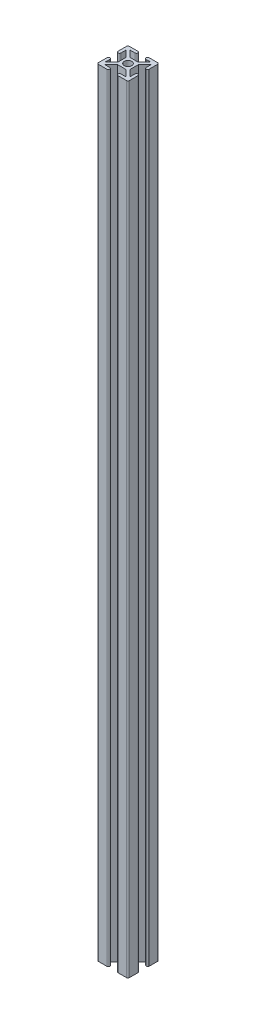
SolidWorks part; units mm, degrees
ref_plane "Alzado" through (0, 0, 0) normal (0, 0, 1) x (1, 0, 0)
ref_plane "Planta" through (0, 0, 0) normal (0, 1, 0) x (1, 0, 0)
ref_plane "Vista lateral" through (0, 0, 0) normal (1, 0, 0) x (0, 0, -1)
sketch "Croquis1" plane through (0, 0, 0) normal (0, 1, 0) x (1, 0, 0)
  line L0 (-15.8949, 10.1863) -> (-15.8949, 11.6113) construction
  line L1 (3.158, -5.9637) -> (7.883, -5.9637)
  line L2 (-17.3199, 19.7613) -> (-17.3199, 11.6113)
  line L3 (-15.8949, 21.1863) -> (-7.7449, 21.1863)
  line L4 (3.1051, 21.1863) -> (11.2551, 21.1863)
  line L5 (-12.417, -5.9637) -> (-7.692, -5.9637)
  line L6 (-8.3199, 10.1863) -> (-8.3199, 2.1863)
  line L7 (-17.267, 0.7613) -> (-17.267, -7.3887)
  line L8 (-15.8684, -8.7872) -> (-7.692, -8.8137)
  line L9 (12.6801, 19.7613) -> (12.6801, 11.715)
  line L10 (-14.4699, 16.3363) -> (-14.4699, 11.6113)
  line L11 (12.6801, 0.865) -> (12.6801, -7.3887)
  line L12 (-6.3199, 19.7613) -> (-7.7449, 19.7613) construction
  line L13 (3.158, -8.8137) -> (11.2551, -8.8137)
  line L14 (-12.4699, 18.3363) -> (-7.7449, 18.3363)
  line L15 (-14.4699, 0.7613) -> (-14.4699, -3.9637)
  line L16 (1.6801, 19.7613) -> (3.1051, 19.7613) construction
  line L17 (3.1051, 18.3363) -> (7.8301, 18.3363)
  line L18 (11.2551, 10.29) -> (11.2551, 11.715) construction
  line L19 (-6.3199, 12.1863) -> (-12.4699, 18.3363)
  line L20 (9.8301, 16.3363) -> (9.8301, 11.715)
  line L21 (11.2551, 2.29) -> (11.2551, 0.865) construction
  line L22 (-8.3199, 10.1863) -> (-14.4699, 16.3363)
  line L23 (9.8301, 0.865) -> (9.8301, -3.9637)
  line L24 (1.733, -7.3887) -> (3.158, -7.3887) construction
  line L25 (-8.3199, 2.1863) -> (-14.4699, -3.9637)
  line L26 (-6.3199, 12.1863) -> (1.6801, 12.1863)
  line L27 (1.6801, 12.1863) -> (7.8301, 18.3363)
  line L28 (-15.8684, 2.1863) -> (-15.8684, 0.7613) construction
  line L29 (-12.417, -5.9637) -> (-6.267, 0.1863)
  line L30 (-6.267, 0.1863) -> (1.733, 0.1863)
  line L31 (1.733, 0.1863) -> (7.883, -5.9637)
  line L32 (-6.267, -7.3887) -> (-7.692, -7.3887) construction
  line L33 (3.6801, 2.1863) -> (9.8301, -3.9637)
  line L34 (3.6801, 10.1863) -> (9.8301, 16.3363)
  line L35 (3.6801, 10.1863) -> (3.6801, 2.1863)
  circle A0 centre (-2.267, 6.1863) radius 3.645
  arc A1 (-17.3199, 11.6113) -> (-14.4699, 11.6113) centre (-15.8949, 11.6113) ccw
  arc A2 (-7.7449, 18.3363) -> (-7.7449, 21.1863) centre (-7.7449, 19.7613) ccw
  arc A3 (3.1051, 21.1863) -> (3.1051, 18.3363) centre (3.1051, 19.7613) ccw
  arc A4 (9.8301, 11.715) -> (12.6801, 11.715) centre (11.2551, 11.715) ccw
  arc A5 (12.6801, 0.865) -> (9.8301, 0.865) centre (11.2551, 0.865) ccw
  arc A6 (3.158, -5.9637) -> (3.158, -8.8137) centre (3.158, -7.3887) ccw
  arc A7 (-14.4699, 0.7613) -> (-17.267, 0.7613) centre (-15.8684, 0.7613) ccw
  arc A8 (-7.692, -8.8137) -> (-7.692, -5.9637) centre (-7.692, -7.3887) ccw
  arc A9 (-17.267, -7.3887) -> (-15.8684, -8.7872) centre (-15.8684, -7.3887) ccw
  arc A10 (11.2551, -8.8137) -> (12.6801, -7.3887) centre (11.2551, -7.3887) ccw
  arc A11 (12.6801, 19.7613) -> (11.2551, 21.1863) centre (11.2551, 19.7613) ccw
  arc A12 (-15.8949, 21.1863) -> (-17.3199, 19.7613) centre (-15.8949, 19.7613) ccw
  dimension "D1" = 7.29
  dimension "D2" = 1.425
  dimension "D3" = 1.425
  dimension "D4" = 1.425
  dimension "D5" = 1.425
  dimension "D6" = 1.425
  dimension "D7" = 1.425
  dimension "D8" = 1.425
  dimension "D9" = 1.425
extrude "Saliente-Extruir1" add sketch "Croquis1" along normal blind 750
sketch "Croquis2" plane through (3.6801, 0, 0) normal (1, 0, 0) x (0, 0, -1)
  line L0 (2.1863, 0) -> (10.1863, 0) construction
  circle A0 centre (6.1863, 18.84) radius 4
  point P4 (6.1863, 0)
  dimension "D1" = 8
  dimension "D2" = 18.84
  dimension "D3" = 0
extrude "Cortar-Extruir1" cut sketch "Croquis2" against normal blind 750
sketch "Croquis3" plane through (-8.3199, 0, 0) normal (-1, 0, 0) x (0, 0, 1)
  circle A0 centre (-6.1863, 75.14) radius 4
  arc A1 (-2.1863, 18.8593) -> (-2.1863, 18.8207) centre (-6.1863, 18.84) ccw construction
  dimension "D1" = 8
  dimension "D2" = 56.3
extrude "Cortar-Extruir2" cut sketch "Croquis3" against normal blind 750
sketch "Croquis4" plane through (-8.3199, 0, 0) normal (-1, 0, 0) x (0, 0, 1)
  circle A0 centre (-6.1863, 255.14) radius 4
  arc A1 (-2.1863, 75.1593) -> (-2.1863, 75.1207) centre (-6.1863, 75.14) ccw construction
  circle A2 centre (-6.1863, 311.44) radius 4
  dimension "D2" = 8
  dimension "D4" = 8
  dimension "D1" = 180
  dimension "D3" = 56.3
extrude "Cortar-Extruir3" cut sketch "Croquis4" against normal blind 750
sketch "Croquis5" plane through (-8.3199, 0, 0) normal (-1, 0, 0) x (0, 0, 1)
  circle A0 centre (-6.1863, 198.84) radius 4
  arc A1 (-2.1863, 18.8593) -> (-2.1863, 18.8207) centre (-6.1863, 18.84) ccw construction
  dimension "D1" = 8
  dimension "D2" = 180
extrude "Cortar-Extruir4" cut sketch "Croquis5" against normal blind 750
sketch "Sketch1" plane through (-8.3199, 0, 0) normal (-1, 0, 0) x (0, 0, 1)
  circle A0 centre (-6.2392, 735) radius 3
  dimension "D1" = 6
extrude "Cut-Extrude1" cut sketch "Sketch1" against normal blind 20
